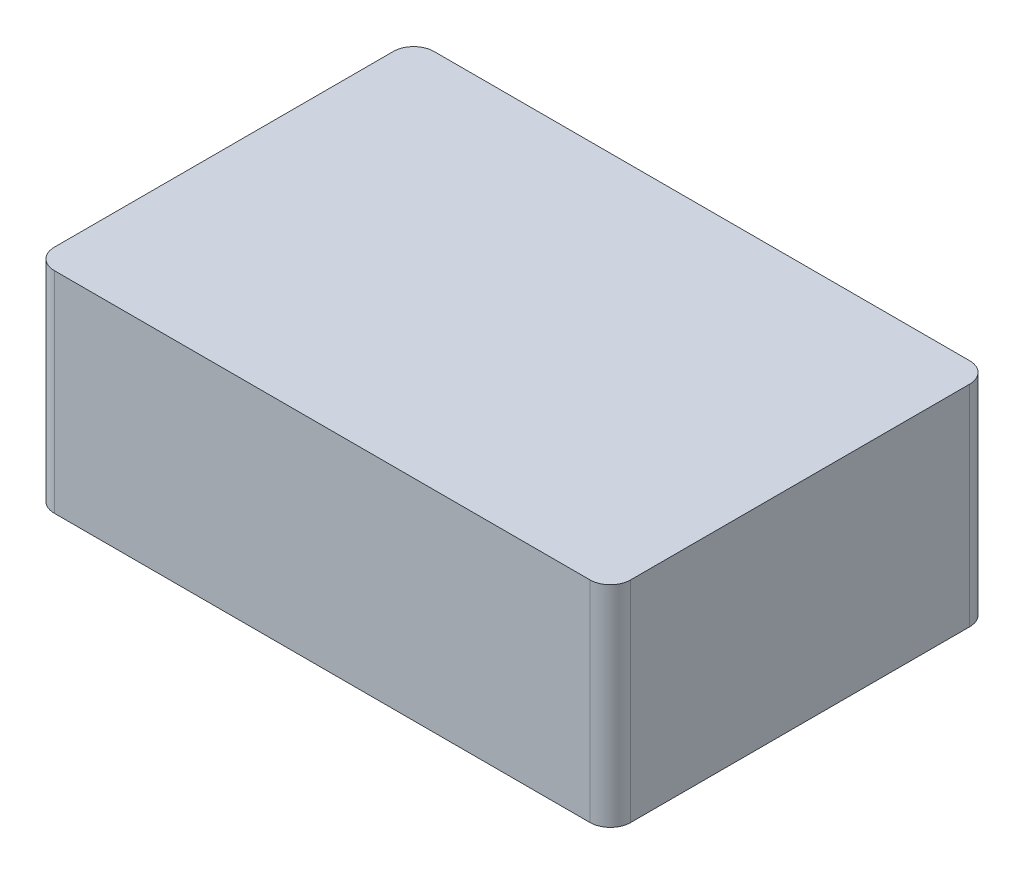
SolidWorks part; units mm, degrees
ref_plane "Front Plane" through (0, 0, 0) normal (0, 0, 1) x (1, 0, 0)
ref_plane "Top Plane" through (0, 0, 0) normal (0, 1, 0) x (1, 0, 0)
ref_plane "Right Plane" through (0, 0, 0) normal (1, 0, 0) x (0, 0, -1)
sketch "Sketch1" plane through (0, 0, 0) normal (0, 1, 0) x (1, 0, 0)
  line L1 (0, 0) -> (85, 0)
  line L2 (0, 0) -> (0, -56)
  line L3 (0, -56) -> (85, -56)
  line L4 (85, 0) -> (85, -56)
  dimension "D1" = 85
  dimension "D2" = 56
extrude "Boss-Extrude1" add sketch "Sketch1" along normal blind 31
fillet "Fillet1" radius 3 4 edges at (0, 15.5, 0) (85, 15.5, 0) (85, 15.5, 56) (0, 15.5, 56)
